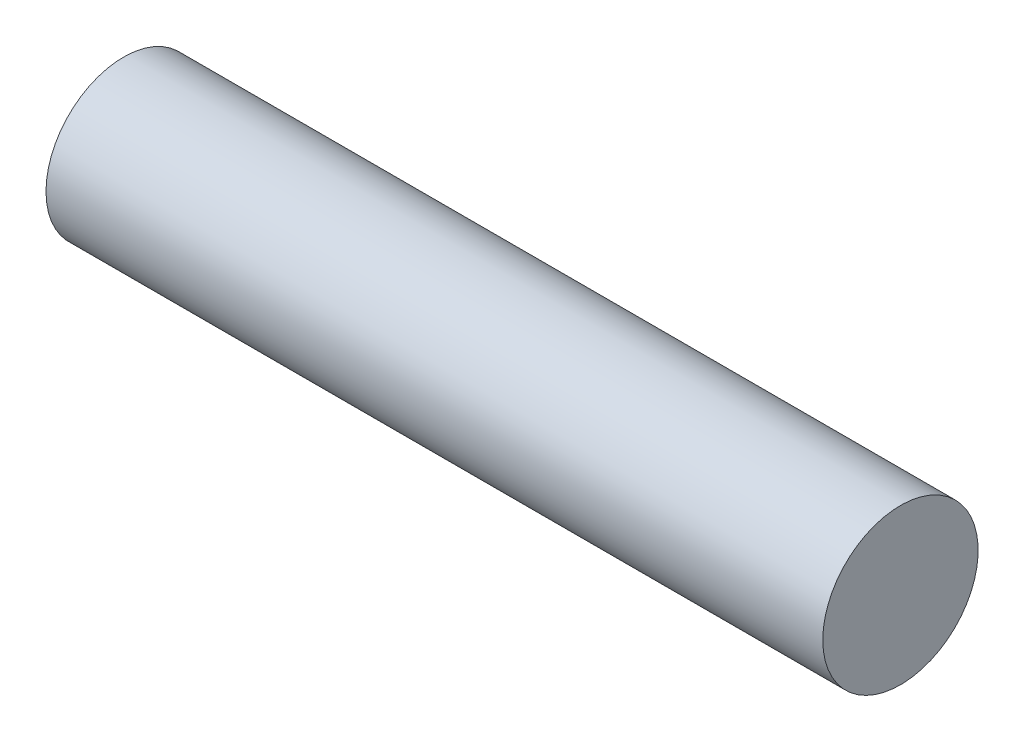
SolidWorks part; units mm, degrees
ref_plane "Plan de face" through (0, 0, 0) normal (0, 0, 1) x (1, 0, 0)
ref_plane "Plan de dessus" through (0, 0, 0) normal (0, 1, 0) x (1, 0, 0)
ref_plane "Plan de droite" through (0, 0, 0) normal (1, 0, 0) x (0, 0, -1)
sketch "Esquisse1" plane through (0, 0, 0) normal (0, 0, 1) x (1, 0, 0)
  line L0 (0, 0) -> (300, 0)
  line L1 (300, 0) -> (300, 30)
  line L2 (300, 30) -> (0, 30)
  line L3 (0, 30) -> (0, 0)
  dimension "D1" = 30
  dimension "D2" = 300
revolve "Révolution1" add sketch "Esquisse1" angle 360 about L0
